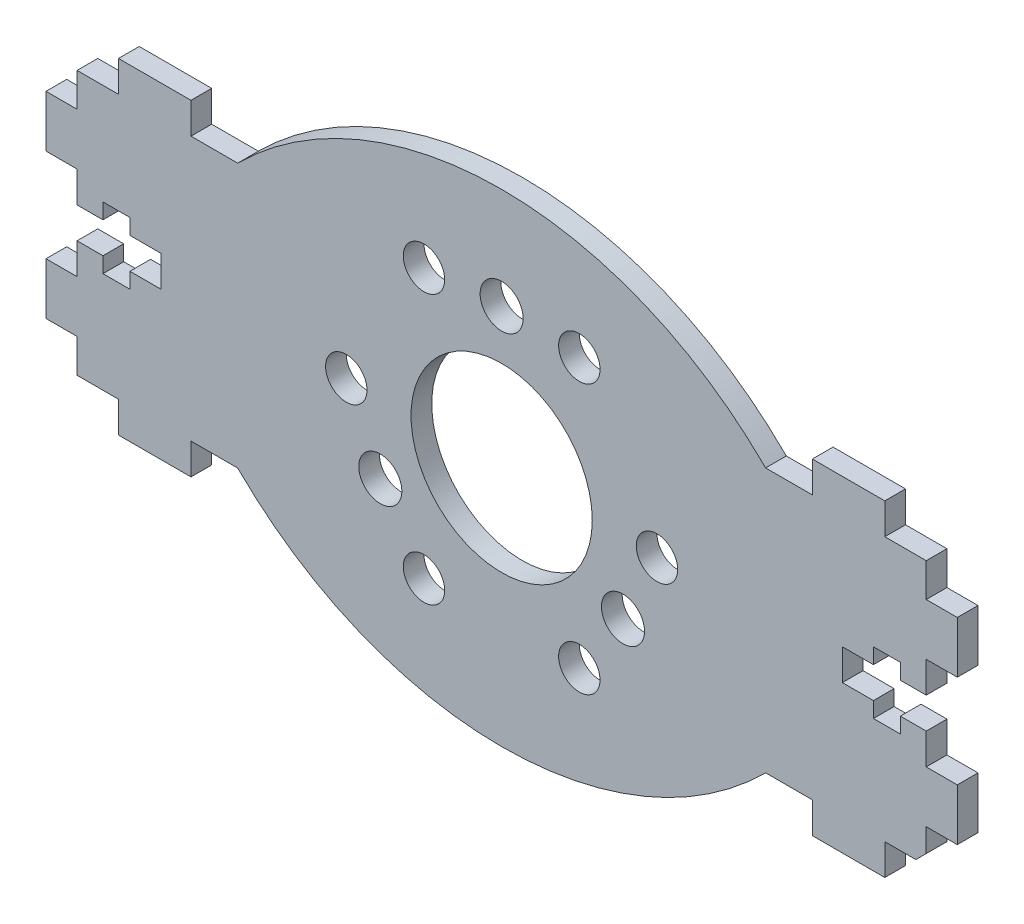
SolidWorks part; units mm, degrees
ref_plane "前视基准面" through (0, 0, 0) normal (0, 0, 1) x (1, 0, 0)
ref_plane "上视基准面" through (0, 0, 0) normal (0, 1, 0) x (1, 0, 0)
ref_plane "右视基准面" through (0, 0, 0) normal (1, 0, 0) x (0, 0, -1)
sketch "草图1" plane through (0, 0, 0) normal (0, 0, 1) x (1, 0, 0)
  line L205 (-30, 12.75) -> (-25.489, 12.75)
  line L238 (-30, -12.75) -> (-25.489, -12.75)
  line L269 (25.489, -12.75) -> (30, -12.75)
  line L270 (25.489, 12.75) -> (30, 12.75)
  line L275 (37, -15.75) -> (30, -15.75)
  line L286 (30, -12.75) -> (30, -15.75)
  line L287 (37, -15.75) -> (37, -12.75)
  line L288 (37, -12.75) -> (40, -12.75)
  line L291 (37, 12.75) -> (41, 12.75)
  line L292 (37, 15.75) -> (37, 12.75)
  line L293 (30, 12.75) -> (30, 15.75)
  line L304 (37, 15.75) -> (30, 15.75)
  line L359 (41, -4.5) -> (44, -4.5)
  line L360 (44, -4.5) -> (44, -9.5)
  line L361 (44, -9.5) -> (41, -9.5)
  line L362 (41, -9.5) -> (41, -11.75)
  line L363 (41, 9.5) -> (41, 12.75)
  line L364 (44, 9.5) -> (41, 9.5)
  line L365 (44, 4.5) -> (44, 9.5)
  line L366 (41, 4.5) -> (44, 4.5)
  line L368 (-41, 4.5) -> (-44, 4.5)
  line L369 (-44, 4.5) -> (-44, 9.5)
  line L370 (-44, 9.5) -> (-41, 9.5)
  line L371 (-41, 9.5) -> (-41, 12.75)
  line L372 (-41, -9.5) -> (-41, -12.75)
  line L373 (-44, -9.5) -> (-41, -9.5)
  line L374 (-44, -4.5) -> (-44, -9.5)
  line L375 (-41, -4.5) -> (-44, -4.5)
  line L376 (-37, 15.75) -> (-30, 15.75)
  line L378 (-30, 12.75) -> (-30, 15.75)
  line L379 (-37, 15.75) -> (-37, 12.75)
  line L380 (-37, 12.75) -> (-41, 12.75)
  line L381 (-37, -12.75) -> (-41, -12.75)
  line L382 (-37, -15.75) -> (-37, -12.75)
  line L383 (-30, -12.75) -> (-30, -15.75)
  line L385 (-37, -15.75) -> (-30, -15.75)
  line L389 (38.5, 3) -> (35.9, 3)
  line L390 (35.9, 3) -> (35.9, 1.5)
  line L391 (35.9, 1.5) -> (32.9, 1.5)
  line L392 (35.9, -1.5) -> (32.9, -1.5)
  line L393 (35.9, -3) -> (35.9, -1.5)
  line L394 (38.5, -3) -> (35.9, -3)
  line L395 (38.5, 1.5) -> (38.5, 3)
  line L396 (32.9, 1.5) -> (32.9, -1.5)
  line L397 (38.5, -1.5) -> (38.5, -3)
  line L398 (38.5, 1.5) -> (41, 1.5)
  line L399 (0, 0) -> (0, -2.02) construction
  line L400 (38.5, -1.5) -> (41, -1.5)
  line L401 (-41, -1.5) -> (-41, -4.5)
  line L402 (41, 4.5) -> (41, 1.5)
  line L403 (41, -1.5) -> (41, -4.5)
  line L404 (-41, 4.5) -> (-41, 1.5)
  line L405 (-38.5, -1.5) -> (-41, -1.5)
  line L406 (-38.5, 1.5) -> (-41, 1.5)
  line L407 (-38.5, -1.5) -> (-38.5, -3)
  line L408 (-32.9, 1.5) -> (-32.9, -1.5)
  line L409 (-38.5, 1.5) -> (-38.5, 3)
  line L410 (-38.5, -3) -> (-35.9, -3)
  line L411 (-35.9, -3) -> (-35.9, -1.5)
  line L412 (-35.9, -1.5) -> (-32.9, -1.5)
  line L413 (-35.9, 1.5) -> (-32.9, 1.5)
  line L414 (-35.9, 3) -> (-35.9, 1.5)
  line L415 (-38.5, 3) -> (-35.9, 3)
  line L416 (40, -12.75) -> (41, -11.75)
  circle A13 centre (0, 0) radius 15 construction
  circle A14 centre (0, 0) radius 13.53 construction
  circle A15 centre (-15, 0) radius 2
  circle A16 centre (-7.5, 12.9904) radius 2
  circle A17 centre (7.5, 12.9904) radius 2
  circle A18 centre (15, 0) radius 2
  circle A19 centre (7.5, -12.9904) radius 2
  circle A20 centre (-7.5, -12.9904) radius 2
  circle A21 centre (0, 13.53) radius 2.08
  circle A22 centre (11.7173, -6.765) radius 2.08
  circle A23 centre (-11.7173, -6.765) radius 2.08
  circle A24 centre (0, 0) radius 8.75
  arc A25 (25.489, 12.75) -> (-25.489, 12.75) centre (0, -12.739) ccw
  arc A26 (25.489, -12.75) -> (-25.489, -12.75) centre (0, 12.739) cw
  point P37 (41, -12.75)
  dimension "D1" = 6
  dimension "D2" = 3
extrude "凸台-拉伸2" add sketch "草图1" along normal blind 2
sketch "草图2" plane through (-41, 0, 0) normal (-1, 0, 0) x (0, 0, 1)
  line L0 (1, 1.5) -> (1, -1.5)
  line L1 (2, 1.5) -> (0, 1.5) construction
  line L2 (2, -1.5) -> (0, -1.5) construction
  circle A0 centre (1, 0) radius 1.5
sketch "草图3" plane through (41, 0, 0) normal (1, 0, 0) x (0, 0, -1)
  line L0 (-1, 1.5) -> (-1, -1.5)
  line L1 (-2, 1.5) -> (0, 1.5) construction
  line L2 (-2, -1.5) -> (0, -1.5) construction
  circle A0 centre (-1, 0) radius 1.5
